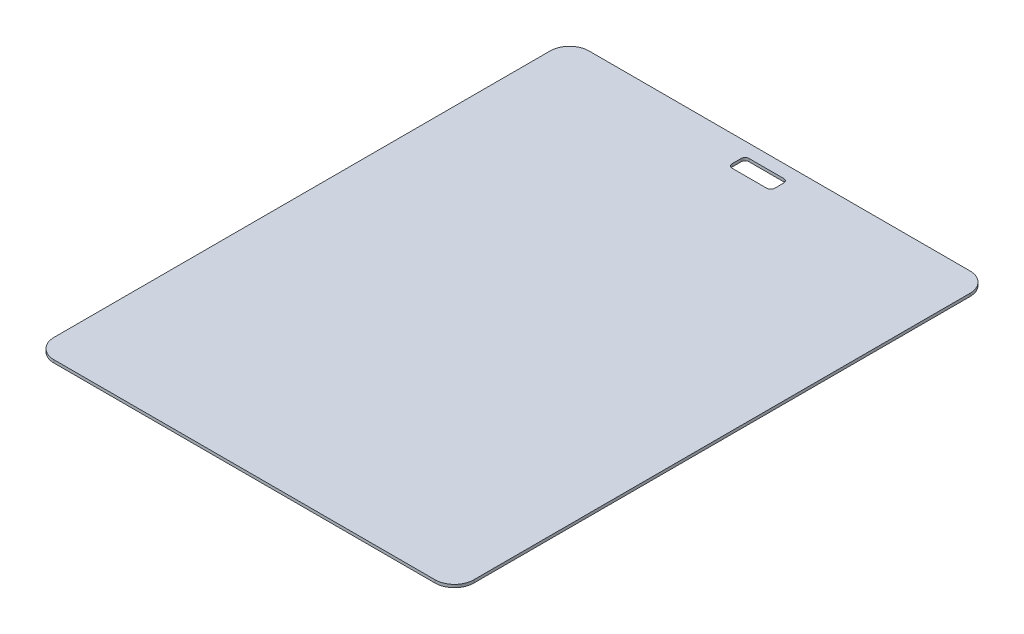
SolidWorks part; units mm, degrees
ref_plane "Front Plane" through (0, 0, 0) normal (0, 0, 1) x (1, 0, 0)
ref_plane "Top Plane" through (0, 0, 0) normal (0, 1, 0) x (1, 0, 0)
ref_plane "Right Plane" through (0, 0, 0) normal (1, 0, 0) x (0, 0, -1)
sketch "Sketch1" plane through (0, 0, 0) normal (0, 1, 0) x (1, 0, 0)
  line L0 (0, 0) -> (0, 147.5) construction
  line L1 (-108.5, 147.5) -> (108.5, 147.5)
  line L2 (-108.5, 147.5) -> (-108.5, -129)
  line L3 (-108.5, -129) -> (108.5, -129)
  line L4 (108.5, 147.5) -> (108.5, -129)
  line L5 (0, -55) -> (0, 55) construction
  dimension "D1" = 147.5
  dimension "D2" = 129
  dimension "D3" = 217
extrude "Boss-Extrude1" add sketch "Sketch1" along normal blind 1.5
sketch "Sketch2" plane through (0, 1.5, 0) normal (0, 1, 0) x (1, 0, 0)
  line L0 (0, 0) -> (-101.6, 0) construction
  line L1 (-101.6, 101.6) -> (101.6, 101.6)
  line L2 (-101.6, 101.6) -> (-101.6, -101.6)
  line L3 (-101.6, -101.6) -> (101.6, -101.6)
  line L4 (101.6, 101.6) -> (101.6, -101.6)
  line L5 (0, 0) -> (0, 101.6) construction
  dimension "D1" = 203.2
fillet "Fillet1" radius 10 4 edges at (108.5, 0.75, -147.5) (-108.5, 0.75, -147.5) (108.5, 0.75, 129) (-108.5, 0.75, 129)
sketch "Sketch4" plane through (0, 1.5, 0) normal (0, 1, 0) x (1, 0, 0)
  line L0 (0, 0) -> (0, 180.6596) construction
  line L1 (-11, 140.73) -> (11, 140.73)
  line L3 (-11, 140.73) -> (-11, 131.98)
  line L4 (-11, 131.98) -> (11, 131.98)
  line L5 (11, 140.73) -> (11, 131.98)
  line L6 (-11, 136.48) -> (-82.9154, 136.48) construction
  dimension "D1" = 22
  dimension "D2" = 4.5
  dimension "D3" = 4.25
  dimension "D4" = 136.48
extrude "Cut-Extrude2" cut sketch "Sketch4" against normal through all
fillet "Fillet2" radius 2 4 edges at (-11, 0.75, -131.98) (11, 0.75, -131.98) (11, 0.75, -140.73) (-11, 0.75, -140.73)
sketch "Sketch5" plane through (0, 1.5, 0) normal (0, 1, 0) x (1, 0, 0)
  line L0 (-108.5, 137.5) -> (-108.5, -119) construction
  line L1 (-98.5, -129) -> (98.5, -129) construction
  circle A0 centre (-107.5, -128) radius 0.535
  circle A1 centre (-104.96, -128) radius 0.535
  circle A2 centre (-102.42, -128) radius 0.535
  circle A3 centre (-99.88, -128) radius 0.535
  circle A4 centre (-97.34, -128) radius 0.535
  circle A5 centre (-94.8, -128) radius 0.535
  circle A6 centre (-92.26, -128) radius 0.535
  circle A7 centre (-89.72, -128) radius 0.535
  circle A8 centre (-87.18, -128) radius 0.535
  circle A9 centre (-84.64, -128) radius 0.535
  circle A10 centre (-82.1, -128) radius 0.535
  circle A11 centre (-79.56, -128) radius 0.535
  circle A12 centre (-77.02, -128) radius 0.535
  circle A13 centre (-74.48, -128) radius 0.535
  circle A14 centre (-71.94, -128) radius 0.535
  circle A15 centre (-69.4, -128) radius 0.535
  circle A16 centre (-66.86, -128) radius 0.535
  circle A17 centre (-64.32, -128) radius 0.535
  circle A18 centre (-61.78, -128) radius 0.535
  circle A19 centre (-59.24, -128) radius 0.535
  circle A20 centre (-56.7, -128) radius 0.535
  circle A21 centre (-54.16, -128) radius 0.535
  circle A22 centre (-51.62, -128) radius 0.535
  circle A23 centre (-49.08, -128) radius 0.535
  circle A24 centre (-46.54, -128) radius 0.535
  circle A25 centre (-44, -128) radius 0.535
  circle A26 centre (-41.46, -128) radius 0.535
  circle A27 centre (-38.92, -128) radius 0.535
  circle A28 centre (-36.38, -128) radius 0.535
  circle A29 centre (-33.84, -128) radius 0.535
  circle A30 centre (-31.3, -128) radius 0.535
  circle A31 centre (-28.76, -128) radius 0.535
  circle A32 centre (-26.22, -128) radius 0.535
  circle A33 centre (-23.68, -128) radius 0.535
  circle A34 centre (-21.14, -128) radius 0.535
  circle A35 centre (-18.6, -128) radius 0.535
  circle A36 centre (-16.06, -128) radius 0.535
  circle A37 centre (-13.52, -128) radius 0.535
  circle A38 centre (-10.98, -128) radius 0.535
  circle A39 centre (-8.44, -128) radius 0.535
  circle A40 centre (-5.9, -128) radius 0.535
  circle A41 centre (-3.36, -128) radius 0.535
  circle A42 centre (-0.82, -128) radius 0.535
  circle A43 centre (1.72, -128) radius 0.535
  circle A44 centre (4.26, -128) radius 0.535
  circle A45 centre (6.8, -128) radius 0.535
  circle A46 centre (9.34, -128) radius 0.535
  circle A47 centre (11.88, -128) radius 0.535
  circle A48 centre (14.42, -128) radius 0.535
  circle A49 centre (16.96, -128) radius 0.535
  circle A50 centre (19.5, -128) radius 0.535
  circle A51 centre (22.04, -128) radius 0.535
  circle A52 centre (24.58, -128) radius 0.535
  circle A53 centre (27.12, -128) radius 0.535
  circle A54 centre (29.66, -128) radius 0.535
  circle A55 centre (32.2, -128) radius 0.535
  circle A56 centre (34.74, -128) radius 0.535
  circle A57 centre (37.28, -128) radius 0.535
  circle A58 centre (39.82, -128) radius 0.535
  circle A59 centre (42.36, -128) radius 0.535
  circle A60 centre (44.9, -128) radius 0.535
  circle A61 centre (47.44, -128) radius 0.535
  circle A62 centre (49.98, -128) radius 0.535
  circle A63 centre (52.52, -128) radius 0.535
  circle A64 centre (55.06, -128) radius 0.535
  circle A65 centre (57.6, -128) radius 0.535
  circle A66 centre (60.14, -128) radius 0.535
  circle A67 centre (62.68, -128) radius 0.535
  circle A68 centre (65.22, -128) radius 0.535
  circle A69 centre (67.76, -128) radius 0.535
  circle A70 centre (70.3, -128) radius 0.535
  circle A71 centre (72.84, -128) radius 0.535
  circle A72 centre (75.38, -128) radius 0.535
  circle A73 centre (77.92, -128) radius 0.535
  circle A74 centre (80.46, -128) radius 0.535
  circle A75 centre (83, -128) radius 0.535
  circle A76 centre (85.54, -128) radius 0.535
  circle A77 centre (88.08, -128) radius 0.535
  circle A78 centre (90.62, -128) radius 0.535
  circle A79 centre (93.16, -128) radius 0.535
  circle A80 centre (95.7, -128) radius 0.535
  circle A81 centre (98.24, -128) radius 0.535
  circle A82 centre (100.78, -128) radius 0.535
  circle A83 centre (103.32, -128) radius 0.535
  circle A84 centre (105.86, -128) radius 0.535
  dimension "D1" = 1.07
  dimension "D2" = 1
  dimension "D3" = 1
  dimension "D5" = 2.54
  dimension "D4" = 85
extrude "Cut-Extrude3" [suppressed] cut sketch "Sketch5" against normal through all
pattern_linear "LPattern1" [suppressed] count 30 spacing 2.5
